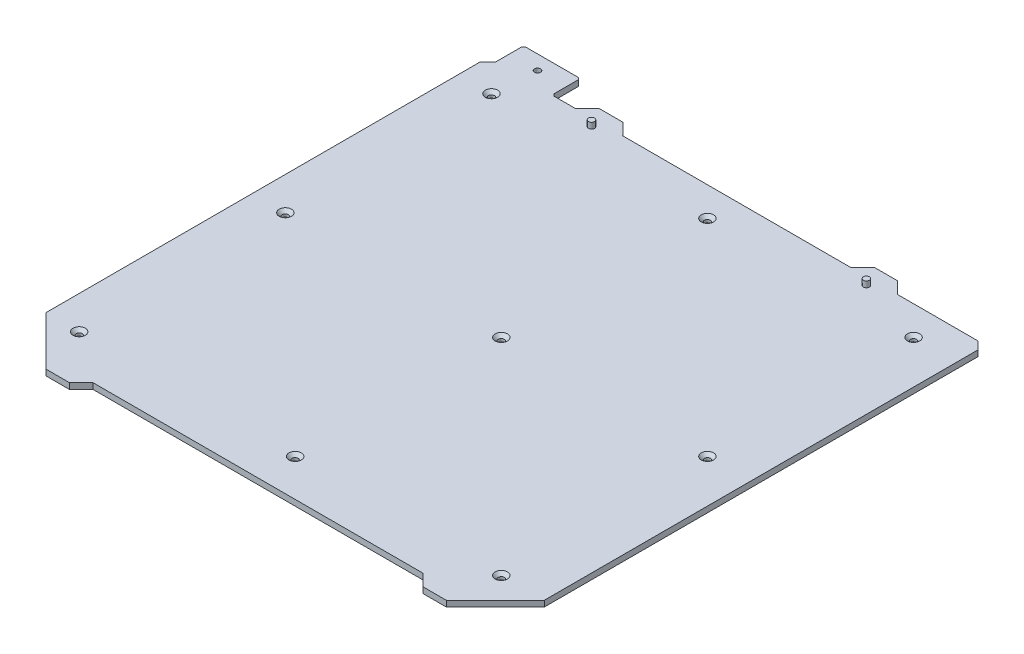
SolidWorks part; units mm, degrees
ref_plane "Front Plane" through (0, 0, 0) normal (0, 0, 1) x (1, 0, 0)
ref_plane "Top Plane" through (0, 0, 0) normal (0, 1, 0) x (1, 0, 0)
ref_plane "Right Plane" through (0, 0, 0) normal (1, 0, 0) x (0, 0, -1)
sketch "Sketch1" plane through (0, 0, 0) normal (0, 1, 0) x (1, 0, 0)
  line L0 (32.0014, 249.4507) -> (32.0036, 249.4507)
  line L1 (32.0036, 249.4507) -> (32.01, 249.4487)
  line L2 (32.01, 249.4487) -> (32.0164, 249.4477)
  line L3 (32.0164, 249.4477) -> (32.0183, 249.4467)
  line L4 (32.0183, 249.4467) -> (32.0204, 249.4457)
  line L5 (32.0204, 249.4457) -> (32.0258, 249.4427)
  line L6 (32.0258, 249.4427) -> (32.0314, 249.4387)
  line L7 (32.0314, 249.4387) -> (32.0329, 249.4377)
  line L8 (32.0329, 249.4377) -> (32.0347, 249.4357)
  line L9 (32.0347, 249.4357) -> (33.0348, 248.4359)
  line L10 (33.0348, 248.4359) -> (33.036, 248.4349)
  line L11 (33.036, 248.4349) -> (33.0377, 248.4329)
  line L12 (33.0377, 248.4329) -> (33.041, 248.4269)
  line L13 (33.041, 248.4269) -> (33.0447, 248.4219)
  line L14 (33.0447, 248.4219) -> (33.0453, 248.4199)
  line L15 (33.0453, 248.4199) -> (33.0464, 248.4179)
  line L16 (33.0464, 248.4179) -> (33.0475, 248.4119)
  line L17 (33.0475, 248.4119) -> (33.0492, 248.4049)
  line L18 (33.0492, 248.4049) -> (33.049, 248.4029)
  line L19 (33.049, 248.4029) -> (33.0494, 248.4009)
  line L20 (33.0494, 248.4009) -> (33.0494, 236.0219)
  line L21 (33.0494, 236.0219) -> (33.9746, 235.097)
  line L22 (33.9746, 235.097) -> (33.9995, 235.101)
  line L23 (33.9995, 235.101) -> (44.9995, 235.101)
  line L24 (44.9995, 235.101) -> (45.0244, 235.097)
  line L25 (45.0244, 235.097) -> (50.9629, 241.0372)
  line L26 (50.9629, 241.0372) -> (50.9647, 241.0392)
  line L27 (50.9647, 241.0392) -> (50.9662, 241.0402)
  line L28 (50.9662, 241.0402) -> (50.9718, 241.0442)
  line L29 (50.9718, 241.0442) -> (50.9772, 241.0472)
  line L30 (50.9772, 241.0472) -> (50.9793, 241.0482)
  line L31 (50.9793, 241.0482) -> (50.9812, 241.0492)
  line L32 (50.9812, 241.0492) -> (50.9876, 241.0502)
  line L33 (50.9876, 241.0502) -> (50.9939, 241.0522)
  line L34 (50.9939, 241.0522) -> (50.9961, 241.0522)
  line L35 (50.9961, 241.0522) -> (50.9983, 241.0522)
  line L36 (50.9983, 241.0522) -> (62.9983, 241.0522)
  line L37 (62.9983, 241.0522) -> (63.0005, 241.0522)
  line L38 (63.0005, 241.0522) -> (63.0027, 241.0522)
  line L39 (63.0027, 241.0522) -> (63.009, 241.0502)
  line L40 (63.009, 241.0502) -> (63.0154, 241.0492)
  line L41 (63.0154, 241.0492) -> (63.0173, 241.0482)
  line L42 (63.0173, 241.0482) -> (63.0194, 241.0472)
  line L43 (63.0194, 241.0472) -> (63.0248, 241.0442)
  line L44 (63.0248, 241.0442) -> (63.0304, 241.0402)
  line L45 (63.0304, 241.0402) -> (63.0319, 241.0392)
  line L46 (63.0319, 241.0392) -> (63.0337, 241.0372)
  line L47 (63.0337, 241.0372) -> (68.9739, 235.0988)
  line L48 (68.9739, 235.0988) -> (68.9988, 235.1028)
  line L49 (68.9988, 235.1028) -> (184.9988, 235.1028)
  line L50 (184.9988, 235.1028) -> (185.0238, 235.0988)
  line L51 (185.0238, 235.0988) -> (190.9624, 241.0391)
  line L52 (190.9624, 241.0391) -> (190.9634, 241.0411)
  line L53 (190.9634, 241.0411) -> (190.9654, 241.0421)
  line L54 (190.9654, 241.0421) -> (190.9714, 241.0461)
  line L55 (190.9714, 241.0461) -> (190.9764, 241.0491)
  line L56 (190.9764, 241.0491) -> (190.9784, 241.0501)
  line L57 (190.9784, 241.0501) -> (190.9804, 241.0511)
  line L58 (190.9804, 241.0511) -> (190.9864, 241.0521)
  line L59 (190.9864, 241.0521) -> (190.9934, 241.0541)
  line L60 (190.9934, 241.0541) -> (190.9954, 241.0541)
  line L61 (190.9954, 241.0541) -> (190.9974, 241.0541)
  line L62 (190.9974, 241.0541) -> (202.9974, 241.0541)
  line L63 (202.9974, 241.0541) -> (202.9994, 241.0541)
  line L64 (202.9994, 241.0541) -> (203.0015, 241.0541)
  line L65 (203.0015, 241.0541) -> (203.0085, 241.0521)
  line L66 (203.0085, 241.0521) -> (203.0145, 241.0511)
  line L67 (203.0145, 241.0511) -> (203.0165, 241.0501)
  line L68 (203.0165, 241.0501) -> (203.0185, 241.0491)
  line L69 (203.0185, 241.0491) -> (203.0235, 241.0461)
  line L70 (203.0235, 241.0461) -> (203.0294, 241.0422)
  line L71 (203.0294, 241.0422) -> (203.0314, 241.0412)
  line L72 (203.0314, 241.0412) -> (203.0325, 241.0392)
  line L73 (203.0325, 241.0392) -> (208.9728, 235.1005)
  line L74 (208.9728, 235.1005) -> (208.9978, 235.1045)
  line L75 (208.9978, 235.1045) -> (249.9978, 235.1045)
  line L76 (249.9978, 235.1045) -> (250.0018, 235.1035)
  line L77 (250.0018, 235.1035) -> (250.0068, 235.1045)
  line L78 (250.0068, 235.1045) -> (250.0188, 235.1005)
  line L79 (250.0188, 235.1005) -> (250.0318, 235.0985)
  line L80 (250.0318, 235.0985) -> (250.0358, 235.0966)
  line L81 (250.0358, 235.0966) -> (250.0398, 235.0956)
  line L82 (250.0398, 235.0956) -> (250.0508, 235.0876)
  line L83 (250.0508, 235.0876) -> (250.0618, 235.0816)
  line L84 (250.0618, 235.0816) -> (250.0648, 235.0776)
  line L85 (250.0648, 235.0776) -> (250.0688, 235.0756)
  line L86 (250.0688, 235.0756) -> (254.0694, 231.0762)
  line L87 (254.0694, 231.0762) -> (254.0714, 231.0722)
  line L88 (254.0714, 231.0722) -> (254.0754, 231.0692)
  line L89 (254.0754, 231.0692) -> (254.0814, 231.0582)
  line L90 (254.0814, 231.0582) -> (254.0894, 231.0472)
  line L91 (254.0894, 231.0472) -> (254.0904, 231.0432)
  line L92 (254.0904, 231.0432) -> (254.0924, 231.0392)
  line L93 (254.0924, 231.0392) -> (254.0944, 231.0262)
  line L94 (254.0944, 231.0262) -> (254.0984, 231.0142)
  line L95 (254.0984, 231.0142) -> (254.0974, 231.0092)
  line L96 (254.0974, 231.0092) -> (254.0984, 231.0052)
  line L97 (254.0984, 231.0052) -> (254.0984, 10.0052)
  line L98 (254.0984, 10.0052) -> (254.0974, 10.0008)
  line L99 (254.0974, 10.0008) -> (254.0984, 9.9964)
  line L100 (254.0984, 9.9964) -> (254.0963, 9.9883)
  line L101 (254.0963, 9.9883) -> (254.0943, 9.9755)
  line L102 (254.0943, 9.9755) -> (254.0923, 9.9716)
  line L103 (254.0923, 9.9716) -> (254.0913, 9.9674)
  line L104 (254.0913, 9.9674) -> (254.0833, 9.9567)
  line L105 (254.0833, 9.9567) -> (254.0773, 9.9454)
  line L106 (254.0773, 9.9454) -> (254.0733, 9.9425)
  line L107 (254.0733, 9.9425) -> (254.0713, 9.9389)
  line L108 (254.0713, 9.9389) -> (229.075, -15.0648)
  line L109 (229.075, -15.0648) -> (229.071, -15.0673)
  line L110 (229.071, -15.0673) -> (229.068, -15.0707)
  line L111 (229.068, -15.0707) -> (229.057, -15.0772)
  line L112 (229.057, -15.0772) -> (229.046, -15.0847)
  line L113 (229.046, -15.0847) -> (229.042, -15.0859)
  line L114 (229.042, -15.0859) -> (229.038, -15.0881)
  line L115 (229.038, -15.0881) -> (229.025, -15.0903)
  line L116 (229.025, -15.0903) -> (229.013, -15.0937)
  line L117 (229.013, -15.0937) -> (229.008, -15.0933)
  line L118 (229.008, -15.0933) -> (229.004, -15.0941)
  line L119 (229.004, -15.0941) -> (217.004, -15.0941)
  line L120 (217.004, -15.0941) -> (217, -15.0933)
  line L121 (217, -15.0933) -> (216.995, -15.0937)
  line L122 (216.995, -15.0937) -> (216.9831, -15.0903)
  line L123 (216.9831, -15.0903) -> (216.9701, -15.0881)
  line L124 (216.9701, -15.0881) -> (216.9661, -15.0859)
  line L125 (216.9661, -15.0859) -> (216.9621, -15.0847)
  line L126 (216.9621, -15.0847) -> (216.9511, -15.0772)
  line L127 (216.9511, -15.0772) -> (216.9401, -15.0707)
  line L128 (216.9401, -15.0707) -> (216.9371, -15.0673)
  line L129 (216.9371, -15.0673) -> (216.9331, -15.0648)
  line L130 (216.9331, -15.0648) -> (210.9618, -9.0953)
  line L131 (210.9618, -9.0953) -> (43.0442, -9.0953)
  line L132 (43.0442, -9.0953) -> (37.0744, -15.0669)
  line L133 (37.0744, -15.0669) -> (37.0708, -15.0694)
  line L134 (37.0708, -15.0694) -> (37.068, -15.0728)
  line L135 (37.068, -15.0728) -> (37.0567, -15.0793)
  line L136 (37.0567, -15.0793) -> (37.046, -15.0868)
  line L137 (37.046, -15.0868) -> (37.0417, -15.088)
  line L138 (37.0417, -15.088) -> (37.0379, -15.0902)
  line L139 (37.0379, -15.0902) -> (37.025, -15.0924)
  line L140 (37.025, -15.0924) -> (37.0124, -15.0958)
  line L141 (37.0124, -15.0958) -> (37.008, -15.0954)
  line L142 (37.008, -15.0954) -> (37.0037, -15.0962)
  line L143 (37.0037, -15.0962) -> (25.0037, -15.0962)
  line L144 (25.0037, -15.0962) -> (24.9994, -15.0954)
  line L145 (24.9994, -15.0954) -> (24.995, -15.0958)
  line L146 (24.995, -15.0958) -> (24.9824, -15.0924)
  line L147 (24.9824, -15.0924) -> (24.9695, -15.0902)
  line L148 (24.9695, -15.0902) -> (24.9657, -15.088)
  line L149 (24.9657, -15.088) -> (24.9614, -15.0868)
  line L150 (24.9614, -15.0868) -> (24.9507, -15.0793)
  line L151 (24.9507, -15.0793) -> (24.9394, -15.0728)
  line L152 (24.9394, -15.0728) -> (24.9366, -15.0694)
  line L153 (24.9366, -15.0694) -> (24.933, -15.0669)
  line L154 (24.933, -15.0669) -> (-0.0707, 9.9293)
  line L155 (-0.0707, 9.9293) -> (-0.0732, 9.9329)
  line L156 (-0.0732, 9.9329) -> (-0.0766, 9.9358)
  line L157 (-0.0766, 9.9358) -> (-0.0831, 9.9471)
  line L158 (-0.0831, 9.9471) -> (-0.0906, 9.9578)
  line L159 (-0.0906, 9.9578) -> (-0.0918, 9.962)
  line L160 (-0.0918, 9.962) -> (-0.094, 9.9658)
  line L161 (-0.094, 9.9658) -> (-0.0962, 9.9787)
  line L162 (-0.0962, 9.9787) -> (-0.0996, 9.9913)
  line L163 (-0.0996, 9.9913) -> (-0.0992, 9.9957)
  line L164 (-0.0992, 9.9957) -> (-0.1, 10)
  line L165 (-0.1, 10) -> (-0.1, 231)
  line L166 (-0.1, 231) -> (-0.094, 231.034)
  line L167 (-0.094, 231.034) -> (-0.0766, 231.064)
  line L168 (-0.0766, 231.064) -> (-0.05, 231.087)
  line L169 (-0.05, 231.087) -> (-0.0174, 231.098)
  line L170 (-0.0174, 231.098) -> (0.0174, 231.098)
  line L171 (0.0174, 231.098) -> (0.025, 231.096)
  line L172 (0.025, 231.096) -> (3.9494, 235.0216)
  line L173 (3.9494, 235.0216) -> (3.9494, 248.4006)
  line L174 (3.9494, 248.4006) -> (3.9498, 248.4026)
  line L175 (3.9498, 248.4026) -> (3.9496, 248.4046)
  line L176 (3.9496, 248.4046) -> (3.9513, 248.4116)
  line L177 (3.9513, 248.4116) -> (3.9524, 248.4176)
  line L178 (3.9524, 248.4176) -> (3.9535, 248.4196)
  line L179 (3.9535, 248.4196) -> (3.9541, 248.4216)
  line L180 (3.9541, 248.4216) -> (3.9578, 248.4266)
  line L181 (3.9578, 248.4266) -> (3.9611, 248.4326)
  line L182 (3.9611, 248.4326) -> (3.9628, 248.4346)
  line L183 (3.9628, 248.4346) -> (3.964, 248.4356)
  line L184 (3.964, 248.4356) -> (4.9639, 249.4357)
  line L185 (4.9639, 249.4357) -> (4.9657, 249.4377)
  line L186 (4.9657, 249.4377) -> (4.9671, 249.4387)
  line L187 (4.9671, 249.4387) -> (4.9728, 249.4427)
  line L188 (4.9728, 249.4427) -> (4.9781, 249.4457)
  line L189 (4.9781, 249.4457) -> (4.9802, 249.4467)
  line L190 (4.9802, 249.4467) -> (4.9821, 249.4477)
  line L191 (4.9821, 249.4477) -> (4.9886, 249.4487)
  line L192 (4.9886, 249.4487) -> (4.9949, 249.4507)
  line L193 (4.9949, 249.4507) -> (4.9971, 249.4507)
  line L194 (4.9971, 249.4507) -> (4.9992, 249.4507)
  line L195 (4.9992, 249.4507) -> (31.9992, 249.4507)
  line L196 (31.9992, 249.4507) -> (32.0014, 249.4507)
  line L197 (5.0207, 249.35) -> (4.05, 248.379)
  line L198 (4.05, 248.379) -> (4.05, 235)
  line L199 (4.05, 235) -> (4.0496, 234.998)
  line L200 (4.0496, 234.998) -> (4.0498, 234.996)
  line L201 (4.0498, 234.996) -> (4.0481, 234.989)
  line L202 (4.0481, 234.989) -> (4.047, 234.983)
  line L203 (4.047, 234.983) -> (4.0459, 234.981)
  line L204 (4.0459, 234.981) -> (4.0453, 234.979)
  line L205 (4.0453, 234.979) -> (4.0416, 234.974)
  line L206 (4.0416, 234.974) -> (4.0383, 234.968)
  line L207 (4.0383, 234.968) -> (4.0366, 234.966)
  line L208 (4.0366, 234.966) -> (4.0354, 234.965)
  line L209 (4.0354, 234.965) -> (0.0961, 231.0245)
  line L210 (0.0961, 231.0245) -> (0.1005, 230.9995)
  line L211 (0.1005, 230.9995) -> (0.1005, 10.0409)
  line L212 (0.1005, 10.0409) -> (25.0456, -14.8967)
  line L213 (25.0456, -14.8967) -> (36.9628, -14.8967)
  line L214 (36.9628, -14.8967) -> (42.9326, -8.9251)
  line L215 (42.9326, -8.9251) -> (42.9362, -8.9226)
  line L216 (42.9362, -8.9226) -> (42.939, -8.9193)
  line L217 (42.939, -8.9193) -> (42.9503, -8.9127)
  line L218 (42.9503, -8.9127) -> (42.961, -8.9052)
  line L219 (42.961, -8.9052) -> (42.9653, -8.9041)
  line L220 (42.9653, -8.9041) -> (42.9691, -8.9019)
  line L221 (42.9691, -8.9019) -> (42.982, -8.8996)
  line L222 (42.982, -8.8996) -> (42.9946, -8.8962)
  line L223 (42.9946, -8.8962) -> (42.999, -8.8966)
  line L224 (42.999, -8.8966) -> (43.0033, -8.8958)
  line L225 (43.0033, -8.8958) -> (211.0033, -8.8958)
  line L226 (211.0033, -8.8958) -> (211.0073, -8.8966)
  line L227 (211.0073, -8.8966) -> (211.0123, -8.8962)
  line L228 (211.0123, -8.8962) -> (211.0243, -8.8996)
  line L229 (211.0243, -8.8996) -> (211.0373, -8.9019)
  line L230 (211.0373, -8.9019) -> (211.0413, -8.9041)
  line L231 (211.0413, -8.9041) -> (211.0453, -8.9052)
  line L232 (211.0453, -8.9052) -> (211.0563, -8.9127)
  line L233 (211.0563, -8.9127) -> (211.0673, -8.9192)
  line L234 (211.0673, -8.9192) -> (211.0703, -8.9226)
  line L235 (211.0703, -8.9226) -> (211.0745, -8.9293)
  line L236 (211.0745, -8.9293) -> (217.0457, -14.8988)
  line L237 (217.0457, -14.8988) -> (228.9637, -14.8988)
  line L238 (228.9637, -14.8988) -> (253.9012, 10.0461)
  line L239 (253.9012, 10.0461) -> (253.9012, 230.9637)
  line L240 (253.9012, 230.9637) -> (249.9596, 234.9041)
  line L241 (249.9596, 234.9041) -> (209.0006, 234.9041)
  line L242 (209.0006, 234.9041) -> (208.9666, 234.9101)
  line L243 (208.9666, 234.9101) -> (208.9366, 234.9271)
  line L244 (208.9366, 234.9271) -> (208.9136, 234.9541)
  line L245 (208.9136, 234.9541) -> (208.9026, 234.9871)
  line L246 (208.9026, 234.9871) -> (208.9026, 235.0211)
  line L247 (208.9026, 235.0211) -> (208.9046, 235.0291)
  line L248 (208.9046, 235.0291) -> (202.9787, 240.9532)
  line L249 (202.9787, 240.9532) -> (191.0207, 240.9532)
  line L250 (191.0207, 240.9532) -> (185.0966, 235.0274)
  line L251 (185.0966, 235.0274) -> (185.0986, 235.0194)
  line L252 (185.0986, 235.0194) -> (185.0986, 234.9854)
  line L253 (185.0986, 234.9854) -> (185.0876, 234.9524)
  line L254 (185.0876, 234.9524) -> (185.0646, 234.9254)
  line L255 (185.0646, 234.9254) -> (185.0346, 234.9084)
  line L256 (185.0346, 234.9084) -> (185.0006, 234.9024)
  line L257 (185.0006, 234.9024) -> (69.0006, 234.9024)
  line L258 (69.0006, 234.9024) -> (68.9664, 234.9084)
  line L259 (68.9664, 234.9084) -> (68.9363, 234.9254)
  line L260 (68.9363, 234.9254) -> (68.914, 234.9524)
  line L261 (68.914, 234.9524) -> (68.9021, 234.9854)
  line L262 (68.9021, 234.9854) -> (68.9021, 235.0194)
  line L263 (68.9021, 235.0194) -> (68.9049, 235.0274)
  line L264 (68.9049, 235.0274) -> (62.979, 240.9515)
  line L265 (62.979, 240.9515) -> (51.0204, 240.9515)
  line L266 (51.0204, 240.9515) -> (45.0963, 235.0256)
  line L267 (45.0963, 235.0256) -> (45.0991, 235.0176)
  line L268 (45.0991, 235.0176) -> (45.0991, 234.9836)
  line L269 (45.0991, 234.9836) -> (45.0872, 234.9506)
  line L270 (45.0872, 234.9506) -> (45.0649, 234.9236)
  line L271 (45.0649, 234.9236) -> (45.0348, 234.9066)
  line L272 (45.0348, 234.9066) -> (45.0006, 234.9006)
  line L273 (45.0006, 234.9006) -> (34.0006, 234.9006)
  line L274 (34.0006, 234.9006) -> (33.9664, 234.9066)
  line L275 (33.9664, 234.9066) -> (33.9363, 234.9236)
  line L276 (33.9363, 234.9236) -> (33.914, 234.9506)
  line L277 (33.914, 234.9506) -> (33.9021, 234.9836)
  line L278 (33.9021, 234.9836) -> (33.9021, 235.0176)
  line L279 (33.9021, 235.0176) -> (33.9049, 235.0256)
  line L280 (33.9049, 235.0256) -> (32.9649, 235.9653)
  line L281 (32.9649, 235.9653) -> (32.9637, 235.9663)
  line L282 (32.9637, 235.9663) -> (32.962, 235.9683)
  line L283 (32.962, 235.9683) -> (32.9587, 235.9743)
  line L284 (32.9587, 235.9743) -> (32.955, 235.9793)
  line L285 (32.955, 235.9793) -> (32.9544, 235.9813)
  line L286 (32.9544, 235.9813) -> (32.9533, 235.9833)
  line L287 (32.9533, 235.9833) -> (32.9522, 235.9893)
  line L288 (32.9522, 235.9893) -> (32.9505, 235.9963)
  line L289 (32.9505, 235.9963) -> (32.9507, 235.9983)
  line L290 (32.9507, 235.9983) -> (32.9503, 236.0003)
  line L291 (32.9503, 236.0003) -> (32.9503, 248.3793)
  line L292 (32.9503, 248.3793) -> (31.9793, 249.35)
  line L293 (31.9793, 249.35) -> (5.0207, 249.35)
extrude "Boss-Extrude1" add sketch "Sketch1" along normal blind 3 contours L292 L293 L197 L198 L199 L200 L201 L202 L203 L204 L205 L206 L207 L208 L209 L210 L211 L212 L213 L214 L215 L216 L217 L218 L219 L220 L221 L222 L223 L224 L225 L226 L227 L228 L229 L230 L231 L232 L233 L234 L235 L236 L237 L238 L239 L240 L241 L242 L243 L244 L245
sketch "Sketch2" plane through (0, 3, 0) normal (0, 1, 0) x (1, 0, 0)
  line L0 (196.9997, 231.0032) -> (196.9997, 240.9532) construction
  line L1 (202.9787, 240.9532) -> (191.0207, 240.9532) construction
  line L2 (62.979, 240.9515) -> (51.0204, 240.9515) construction
  line L3 (196.9997, 240.9532) -> (56.9997, 240.9532) construction
  line L4 (196.9997, 240.9532) -> (196.9997, 231.0032) construction
  line L5 (196.9997, 231.0032) -> (56.9997, 231.0032) construction
  line L6 (56.9997, 240.9532) -> (56.9997, 231.0032) construction
  line L7 (18.5, 242) -> (18.5, 249.35) construction
  line L8 (31.9793, 249.35) -> (5.0207, 249.35) construction
  line L9 (43.0033, -8.8958) -> (211.0033, -8.8958) construction
  line L10 (127.0033, 10.0409) -> (127.0033, -8.8958) construction
  line L216 (127.0033, 10.0409) -> (127.0006, 234.9024) construction
  line L217 (185.0006, 234.9024) -> (69.0006, 234.9024) construction
  line L218 (232.0033, 10.0409) -> (232.0006, 234.9041) construction
  line L219 (249.9596, 234.9041) -> (209.0006, 234.9041) construction
  line L220 (17.0033, 10.0409) -> (17.0033, 234.9312) construction
  line L221 (232.002, 115.0409) -> (0.1005, 115.0409) construction
  line L222 (0.1005, 230.9995) -> (0.1005, 10.0409) construction
  line L223 (232.0008, 220.0409) -> (0.1005, 220.0409) construction
  line L224 (232.0033, 10.0409) -> (0.1005, 10.0409) construction
  circle A0 centre (17.0033, 10.0409) radius 1.55
  circle A1 centre (127.0033, 10.0409) radius 1.55
  circle A2 centre (232.0033, 10.0409) radius 1.55
  circle A3 centre (232.002, 115.0409) radius 1.55
  circle A4 centre (232.0008, 220.0409) radius 1.55
  circle A5 centre (127.002, 115.0409) radius 1.55
  circle A6 centre (17.0033, 115.0409) radius 1.55
  circle A7 centre (17.0033, 220.0409) radius 1.55
  circle A8 centre (127.0008, 220.0409) radius 1.55
  circle A9 centre (196.9997, 231.0032) radius 1.55
  circle A10 centre (56.9997, 231.0032) radius 1.55
  circle A11 centre (18.5, 242) radius 1.55
  point P21 (56.9997, 240.9515)
  dimension "D1" = 3.1
  dimension "D2" = 3.1
  dimension "D3" = 3.1
  dimension "D4" = 3.1
  dimension "D5" = 3.1
  dimension "D6" = 3.1
  dimension "D11" = 3.1
  dimension "D12" = 3.1
  dimension "D13" = 3.1
  dimension "D15" = 3.1
  dimension "D16" = 3.1
  dimension "D18" = 3.1
  dimension "D7" = 110
  dimension "D8" = 105
  dimension "D9" = 105
  dimension "D10" = 105
  dimension "D14" = 9.95
  dimension "D17" = 7.35
extrude "Cut-Extrude1" cut sketch "Sketch2" against normal through all
sketch "Sketch3" plane through (0, 0, 0) normal (0, -1, 0) x (1, 0, 0)
  circle A0 centre (56.9997, -231.0032) radius 1.55 construction
  circle A1 centre (196.9997, -231.0032) radius 1.55 construction
  circle A2 centre (56.9997, -231.0032) radius 1.55
  circle A3 centre (196.9997, -231.0032) radius 1.55
extrude "Boss-Extrude3" add sketch "Sketch3" against normal blind 6
ref_plane "Plane1" through (127.0008, 0, 0) normal (-1, 0, 0) x (0, 0, 1)
chamfer "Chamfer1" distance 1.6 angle 45 9 edges at (232.0008, 3, -218.4909) (232.002, 3, -113.4909) (232.0033, 3, -8.4909) (127.0033, 3, -8.4909) (127.002, 3, -113.4909) (127.0008, 3, -218.4909) (17.0033, 3, -218.4909) (17.0033, 3, -113.4909) (17.0033, 3, -8.4909)
